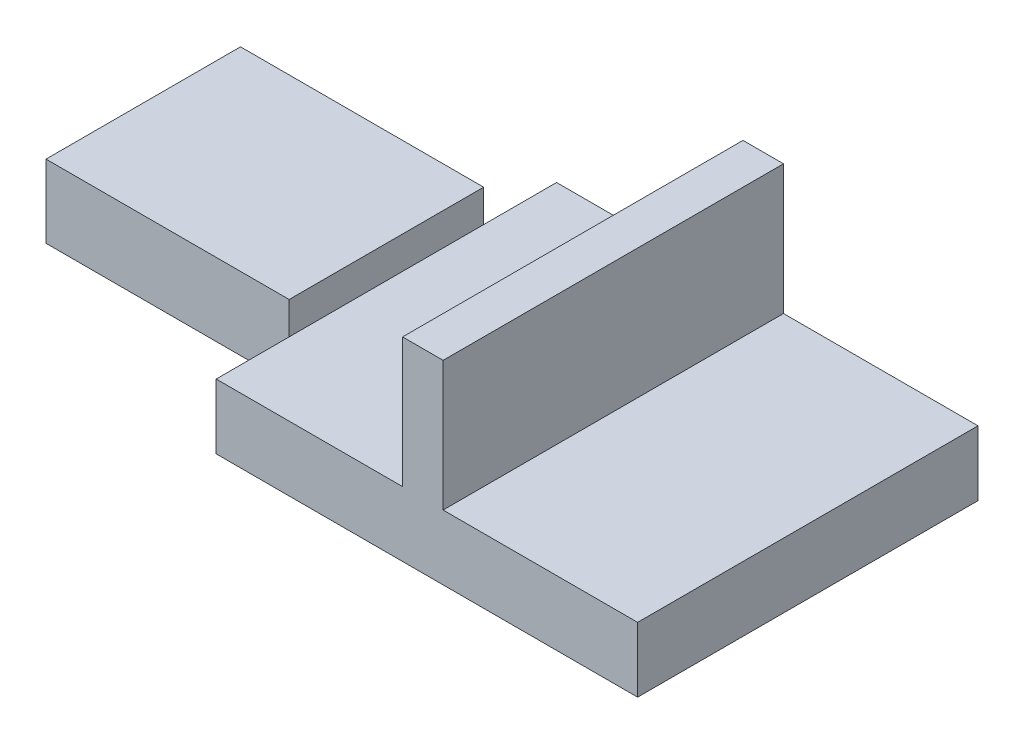
SolidWorks part; units mm, degrees
ref_plane "Front Plane" through (0, 0, 0) normal (0, 0, 1) x (1, 0, 0)
ref_plane "Top Plane" through (0, 0, 0) normal (0, 1, 0) x (1, 0, 0)
ref_plane "Right Plane" through (0, 0, 0) normal (1, 0, 0) x (0, 0, -1)
sketch "Sketch1" plane through (0, 0, 0) normal (0, 0, 1) x (1, 0, 0)
  line L0 (-18.9236, 0) -> (23.1502, 0) construction
  line L1 (1, 2) -> (1, 10)
  line L2 (-13, -2) -> (13, -2)
  line L3 (-13, -2) -> (-13, 2)
  line L4 (-13, 2) -> (-1.5, 2)
  line L5 (13, -2) -> (13, 2)
  line L6 (-13, -2) -> (13, 2) construction
  line L7 (-13, 2) -> (13, -2) construction
  line L11 (-1.5, 10) -> (-1.5, 2)
  line L12 (1, 2) -> (13, 2)
  line L13 (1, 10) -> (-1.5, 10)
  point P3 (0, 0)
  dimension "D1" = 26
  dimension "D2" = 4
  dimension "D3" = 12
  dimension "D4" = 8
  dimension "D6" = 2.5
extrude "Boss-Extrude2" add sketch "Sketch1" along normal blind 21
sketch "Sketch2" plane through (-13, 0, 0) normal (-1, 0, 0) x (0, 0, 1)
  line L0 (-3.0287, -0.5) -> (24.5032, -0.5) construction
  line L1 (21, -2) -> (0, -2) construction
  line L2 (0, 10) -> (0, 2) construction
  line L3 (4.5, -0.5) -> (16.5, -0.5)
  line L4 (4.5, -0.5) -> (4.5, 4)
  line L5 (4.5, 4) -> (16.5, 4)
  line L6 (16.5, -0.5) -> (16.5, 4)
  dimension "D1" = 1.5
  dimension "D2" = 12
  dimension "D3" = 4.5
  dimension "D4" = 4.5
extrude "Boss-Extrude3" add sketch "Sketch2" along normal blind 15
